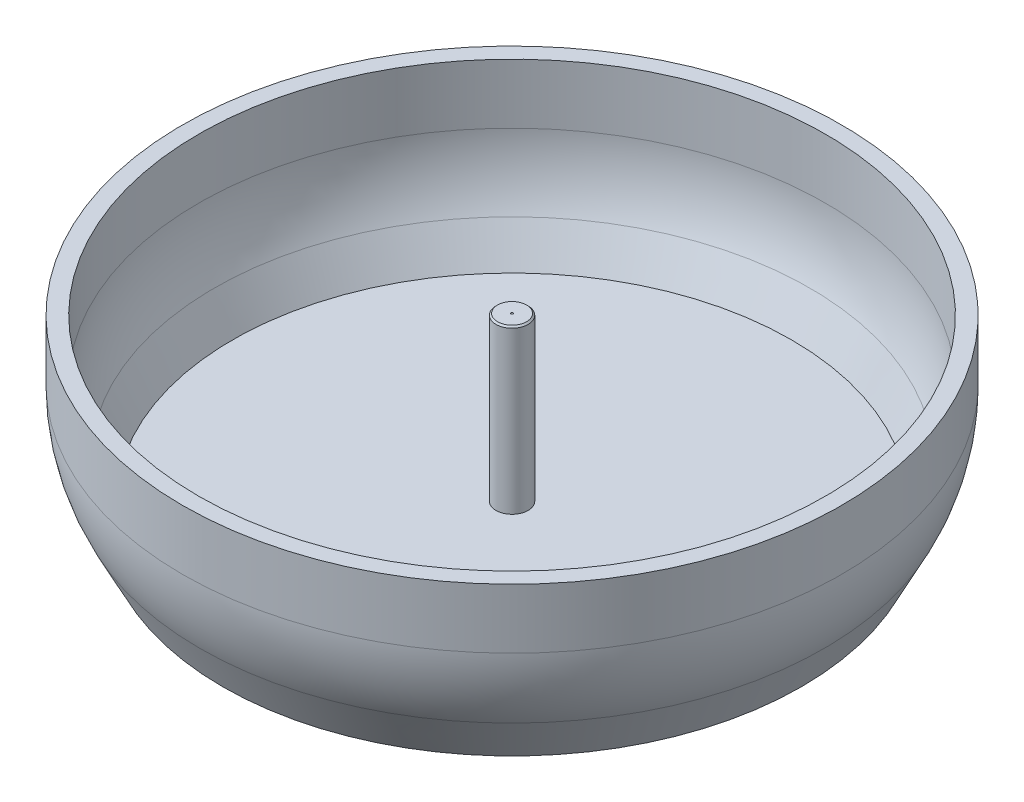
SolidWorks part; units mm, degrees
ref_plane "Alzado" through (0, 0, 0) normal (0, 0, 1) x (1, 0, 0)
ref_plane "Planta" through (0, 0, 0) normal (0, 1, 0) x (1, 0, 0)
ref_plane "Vista lateral" through (0, 0, 0) normal (1, 0, 0) x (0, 0, -1)
sketch "Croquis3" plane through (0, 0, 0) normal (0, 0, 1) x (1, 0, 0)
  line L0 (0, 0) -> (90.1231, 0)
  line L1 (90.1231, 0) -> (97.1956, 13.8721)
  line L2 (102.6509, 36.5826) -> (102.6509, 55.1956)
  line L3 (5, 55.1956) -> (5, 5)
  line L4 (0, 55.1956) -> (0, 0)
  line L5 (5, 5) -> (87.0599, 5)
  line L6 (87.0599, 5) -> (92.7411, 16.1431)
  line L7 (97.6509, 36.5826) -> (97.6509, 55.1956)
  line L8 (5, 55.1956) -> (4.5183, 55.6774)
  line L9 (97.6509, 55.1956) -> (102.6509, 55.1956)
  line L10 (4.5183, 55.6774) -> (0.3359, 55.6774)
  line L11 (0.3359, 55.6774) -> (0, 55.1956)
  arc A0 (97.1956, 13.8721) -> (102.6509, 36.5826) centre (52.6509, 36.5826) ccw
  arc A1 (92.7411, 16.1431) -> (97.6509, 36.5826) centre (52.6509, 36.5826) ccw
  dimension "D1" = 50
  dimension "D2" = 5
revolve "Revolución3" add sketch "Croquis3" angle 360 about L4
